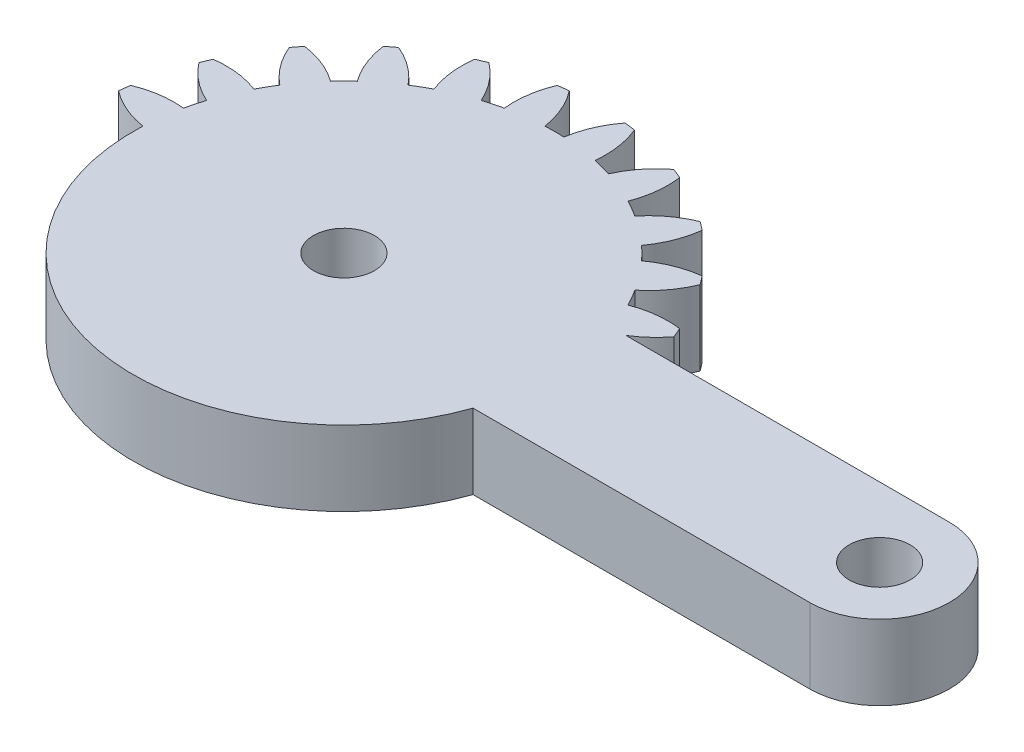
SolidWorks part; units mm, degrees
ref_plane "Front Plane" through (0, 0, 0) normal (0, 0, 1) x (1, 0, 0)
ref_plane "Top Plane" through (0, 0, 0) normal (0, 1, 0) x (1, 0, 0)
ref_plane "Right Plane" through (0, 0, 0) normal (1, 0, 0) x (0, 0, -1)
sketch "Sketch1" plane through (0, 0, 0) normal (0, 1, 0) x (1, 0, 0)
  line L0 (20.6437, 4) -> (2.0816, 4)
  line L1 (2.0816, -4) -> (20.6437, -4)
  arc A0 (2.0816, 4) -> (3.5217, 5.3071) centre (-0.7683, 8.5867) ccw
  arc A1 (3.5217, 5.3071) -> (3.2829, 5.8838) centre (-10.1063, 0) ccw
  arc A2 (3.2829, 5.8838) -> (0.6271, 5.5703) centre (2.5684, 0.5313) ccw
  arc A3 (0.6271, 5.5703) -> (0.0844, 6.5103) centre (-10.1063, 0) ccw
  arc A4 (0.0844, 6.5103) -> (1.6838, 8.6535) centre (-3.3089, 10.711) ccw
  arc A5 (1.6838, 8.6535) -> (1.3038, 9.1487) centre (-10.1063, 0) ccw
  arc A6 (1.3038, 9.1487) -> (-1.1803, 8.1585) centre (1.999, 3.7936) ccw
  arc A7 (-1.1803, 8.1585) -> (-1.9479, 8.926) centre (-10.1063, 0) ccw
  arc A8 (-1.9479, 8.926) -> (-0.9576, 11.4102) centre (-6.3127, 12.1053) ccw
  arc A9 (-0.9576, 11.4102) -> (-1.4528, 11.7901) centre (-10.1063, 0) ccw
  arc A10 (-1.4528, 11.7901) -> (-3.596, 10.1907) centre (0.6046, 6.7975) ccw
  arc A11 (-3.596, 10.1907) -> (-4.5361, 10.7334) centre (-10.1063, 0) ccw
  arc A12 (-4.5361, 10.7334) -> (-4.2225, 13.3892) centre (-9.5751, 12.6747) ccw
  arc A13 (-4.2225, 13.3892) -> (-4.7992, 13.6281) centre (-10.1063, 0) ccw
  arc A14 (-4.7992, 13.6281) -> (-6.4554, 11.5285) centre (-1.5196, 9.3381) ccw
  arc A15 (-6.4554, 11.5285) -> (-7.5039, 11.8094) centre (-10.1063, 0) ccw
  arc A16 (-7.5039, 11.8094) -> (-7.8884, 14.4558) centre (-12.8736, 12.3803) ccw
  arc A17 (-7.8884, 14.4558) -> (-8.5072, 14.5373) centre (-10.1063, 0) ccw
  arc A18 (-8.5072, 14.5373) -> (-9.5636, 12.0806) centre (-4.2291, 11.2423) ccw
  arc A19 (-9.5636, 12.0806) -> (-10.6491, 12.0806) centre (-10.1063, 0) ccw
  arc A20 (-10.6491, 12.0806) -> (-11.7054, 14.5373) centre (-15.9836, 11.2423) ccw
  arc A21 (-11.7054, 14.5373) -> (-12.3243, 14.4558) centre (-10.1063, 0) ccw
  arc A22 (-12.3243, 14.4558) -> (-12.7088, 11.8094) centre (-7.3391, 12.3803) ccw
  arc A23 (-12.7088, 11.8094) -> (-13.7573, 11.5285) centre (-10.1063, 0) ccw
  arc A24 (-13.7573, 11.5285) -> (-15.4135, 13.6281) centre (-18.6931, 9.3381) ccw
  arc A25 (-15.4135, 13.6281) -> (-15.9901, 13.3892) centre (-10.1063, 0) ccw
  arc A26 (-15.9901, 13.3892) -> (-15.6766, 10.7334) centre (-10.6376, 12.6747) ccw
  arc A27 (-15.6766, 10.7334) -> (-16.6166, 10.1907) centre (-10.1063, 0) ccw
  arc A28 (-16.6166, 10.1907) -> (-18.7599, 11.7901) centre (-20.8173, 6.7975) ccw
  arc A29 (-18.7599, 11.7901) -> (-19.255, 11.4102) centre (-10.1063, 0) ccw
  arc A30 (-19.255, 11.4102) -> (-18.2648, 8.926) centre (-13.9, 12.1053) ccw
  arc A31 (-18.2648, 8.926) -> (-19.0324, 8.1585) centre (-10.1063, 0) ccw
  arc A32 (-19.0324, 8.1585) -> (-21.5165, 9.1487) centre (-22.2117, 3.7936) ccw
  arc A33 (-21.5165, 9.1487) -> (-21.8965, 8.6535) centre (-10.1063, 0) ccw
  arc A34 (-21.8965, 8.6535) -> (-20.2971, 6.5103) centre (-16.9038, 10.711) ccw
  arc A35 (-20.2971, 6.5103) -> (-20.8398, 5.5703) centre (-10.1063, 0) ccw
  arc A36 (-20.8398, 5.5703) -> (-23.4956, 5.8838) centre (-22.7811, 0.5313) ccw
  arc A37 (-23.4956, 5.8838) -> (-23.7344, 5.3071) centre (-10.1063, 0) ccw
  arc A38 (-23.7344, 5.3071) -> (-21.6348, 3.6509) centre (-19.4444, 8.5867) ccw
  arc A39 (-21.6348, 3.6509) -> (-21.9157, 2.6025) centre (-10.1063, 0) ccw
  arc A40 (-21.9157, 2.6025) -> (-24.5622, 2.2179) centre (-22.4867, -2.7673) ccw
  arc A41 (-24.5622, 2.2179) -> (-24.6437, 1.5991) centre (-10.1063, 0) ccw
  arc A42 (-24.6437, 1.5991) -> (-22.1869, 0.5427) centre (-21.3486, 5.8773) ccw
  arc A43 (-22.1869, 0.5427) -> (-22.1869, -0.5427) centre (-10.1063, 0) ccw
  arc A44 (-22.1869, -0.5427) -> (-24.6437, -1.5991) centre (-21.3486, -5.8773) ccw
  arc A45 (-24.6437, -1.5991) -> (-24.5622, -2.2179) centre (-10.1063, 0) ccw
  arc A46 (-24.5622, -2.2179) -> (-21.9157, -2.6025) centre (-22.4867, 2.7673) ccw
  arc A47 (-21.9157, -2.6025) -> (-21.6348, -3.6509) centre (-10.1063, 0) ccw
  arc A48 (-21.6348, -3.6509) -> (-23.7344, -5.3071) centre (-19.4444, -8.5867) ccw
  arc A49 (-23.7344, -5.3071) -> (-23.4956, -5.8838) centre (-10.1063, 0) ccw
  arc A50 (-23.4956, -5.8838) -> (-20.8398, -5.5703) centre (-22.7811, -0.5313) ccw
  arc A51 (-20.8398, -5.5703) -> (-20.2971, -6.5103) centre (-10.1063, 0) ccw
  arc A52 (-20.2971, -6.5103) -> (-21.8965, -8.6535) centre (-16.9038, -10.711) ccw
  arc A53 (-21.8965, -8.6535) -> (-21.5165, -9.1487) centre (-10.1063, 0) ccw
  arc A54 (-21.5165, -9.1487) -> (-19.0324, -8.1585) centre (-22.2117, -3.7936) ccw
  arc A55 (-19.0324, -8.1585) -> (-18.2648, -8.926) centre (-10.1063, 0) ccw
  arc A56 (-18.2648, -8.926) -> (-19.255, -11.4102) centre (-13.9, -12.1053) ccw
  arc A57 (-19.255, -11.4102) -> (-18.7599, -11.7901) centre (-10.1063, 0) ccw
  arc A58 (-18.7599, -11.7901) -> (-16.6166, -10.1907) centre (-20.8173, -6.7975) ccw
  arc A59 (-16.6166, -10.1907) -> (-15.6766, -10.7334) centre (-10.1063, 0) ccw
  arc A60 (-15.6766, -10.7334) -> (-15.9901, -13.3892) centre (-10.6376, -12.6747) ccw
  arc A61 (-15.9901, -13.3892) -> (-15.4135, -13.6281) centre (-10.1063, 0) ccw
  arc A62 (-15.4135, -13.6281) -> (-13.7573, -11.5285) centre (-18.6931, -9.3381) ccw
  arc A63 (-13.7573, -11.5285) -> (-12.7088, -11.8094) centre (-10.1063, 0) ccw
  arc A64 (-12.7088, -11.8094) -> (-12.3243, -14.4558) centre (-7.3391, -12.3803) ccw
  arc A65 (-12.3243, -14.4558) -> (-11.7054, -14.5373) centre (-10.1063, 0) ccw
  arc A66 (-11.7054, -14.5373) -> (-10.6491, -12.0806) centre (-15.9836, -11.2423) ccw
  arc A67 (-10.6491, -12.0806) -> (-9.5636, -12.0806) centre (-10.1063, 0) ccw
  arc A68 (-9.5636, -12.0806) -> (-8.5072, -14.5373) centre (-4.2291, -11.2423) ccw
  arc A69 (-8.5072, -14.5373) -> (-7.8884, -14.4558) centre (-10.1063, 0) ccw
  arc A70 (-7.8884, -14.4558) -> (-7.5039, -11.8094) centre (-12.8736, -12.3803) ccw
  arc A71 (-7.5039, -11.8094) -> (-6.4554, -11.5285) centre (-10.1063, 0) ccw
  arc A72 (-6.4554, -11.5285) -> (-4.7992, -13.6281) centre (-1.5196, -9.3381) ccw
  arc A73 (-4.7992, -13.6281) -> (-4.2225, -13.3892) centre (-10.1063, 0) ccw
  arc A74 (-4.2225, -13.3892) -> (-4.5361, -10.7334) centre (-9.5751, -12.6747) ccw
  arc A75 (-4.5361, -10.7334) -> (-3.596, -10.1907) centre (-10.1063, 0) ccw
  arc A76 (-3.596, -10.1907) -> (-1.4528, -11.7901) centre (0.6046, -6.7975) ccw
  arc A77 (-1.4528, -11.7901) -> (-0.9576, -11.4102) centre (-10.1063, 0) ccw
  arc A78 (-0.9576, -11.4102) -> (-1.9479, -8.926) centre (-6.3127, -12.1053) ccw
  arc A79 (-1.9479, -8.926) -> (-1.1803, -8.1585) centre (-10.1063, 0) ccw
  arc A80 (-1.1803, -8.1585) -> (1.3038, -9.1487) centre (1.999, -3.7936) ccw
  arc A81 (1.3038, -9.1487) -> (1.6838, -8.6535) centre (-10.1063, 0) ccw
  arc A82 (1.6838, -8.6535) -> (0.0844, -6.5103) centre (-3.3089, -10.711) ccw
  arc A83 (0.0844, -6.5103) -> (0.6271, -5.5703) centre (-10.1063, 0) ccw
  arc A84 (0.6271, -5.5703) -> (3.2829, -5.8838) centre (2.5684, -0.5313) ccw
  arc A85 (3.2829, -5.8838) -> (3.5217, -5.3071) centre (-10.1063, 0) ccw
  arc A86 (3.5217, -5.3071) -> (2.0816, -4) centre (-0.7683, -8.5867) ccw
  arc A87 (20.6437, -4) -> (20.6437, 4) centre (20.6437, 0) ccw
  circle A88 centre (-10.1063, 0) radius 1.75
  circle A89 centre (20.6437, 0) radius 1.75
  dimension "D1" = 3.5
  dimension "D2" = 3.5
extrude "Boss-Extrude1" add sketch "Sketch1" along normal blind 4.3
sketch "Sketch2" plane through (0, 4.3, 0) normal (0, 1, 0) x (1, 0, 0)
  line L0 (2.0816, -4) -> (1.3057, -4)
  line L2 (20.6437, 4) -> (2.0816, 4)
  line L3 (2.0816, -4) -> (20.6437, -4)
  line L4 (20.6437, 4) -> (2.0816, 4)
  line L5 (2.0816, -4) -> (20.6437, -4)
  circle A0 centre (-10.1063, 0) radius 12.0927
  arc A88 (20.6437, -4) -> (20.6437, 4) centre (20.6437, 0) ccw
  arc A89 (2.0816, 4) -> (3.5217, 5.3071) centre (-0.7683, 8.5867) ccw
  arc A90 (3.5217, 5.3071) -> (3.2829, 5.8838) centre (-10.1063, 0) ccw
  arc A91 (3.2829, 5.8838) -> (0.6271, 5.5703) centre (2.5684, 0.5313) ccw
  arc A92 (0.6271, 5.5703) -> (0.0844, 6.5103) centre (-10.1063, 0) ccw
  arc A93 (0.0844, 6.5103) -> (1.6838, 8.6535) centre (-3.3089, 10.711) ccw
  arc A94 (1.6838, 8.6535) -> (1.3038, 9.1487) centre (-10.1063, 0) ccw
  arc A95 (1.3038, 9.1487) -> (-1.1803, 8.1585) centre (1.999, 3.7936) ccw
  arc A96 (-1.1803, 8.1585) -> (-1.9479, 8.926) centre (-10.1063, 0) ccw
  arc A97 (-1.9479, 8.926) -> (-0.9576, 11.4102) centre (-6.3127, 12.1053) ccw
  arc A98 (-0.9576, 11.4102) -> (-1.4528, 11.7901) centre (-10.1063, 0) ccw
  arc A99 (-1.4528, 11.7901) -> (-3.596, 10.1907) centre (0.6046, 6.7975) ccw
  arc A100 (-3.596, 10.1907) -> (-4.5361, 10.7334) centre (-10.1063, 0) ccw
  arc A101 (-4.5361, 10.7334) -> (-4.2225, 13.3892) centre (-9.5751, 12.6747) ccw
  arc A102 (-4.2225, 13.3892) -> (-4.7992, 13.6281) centre (-10.1063, 0) ccw
  arc A103 (-4.7992, 13.6281) -> (-6.4554, 11.5285) centre (-1.5196, 9.3381) ccw
  arc A104 (-6.4554, 11.5285) -> (-7.5039, 11.8094) centre (-10.1063, 0) ccw
  arc A105 (-7.5039, 11.8094) -> (-7.8884, 14.4558) centre (-12.8736, 12.3803) ccw
  arc A106 (-7.8884, 14.4558) -> (-8.5072, 14.5373) centre (-10.1063, 0) ccw
  arc A107 (-8.5072, 14.5373) -> (-9.5636, 12.0806) centre (-4.2291, 11.2423) ccw
  arc A108 (-9.5636, 12.0806) -> (-10.6491, 12.0806) centre (-10.1063, 0) ccw
  arc A109 (-10.6491, 12.0806) -> (-11.7054, 14.5373) centre (-15.9836, 11.2423) ccw
  arc A110 (-11.7054, 14.5373) -> (-12.3243, 14.4558) centre (-10.1063, 0) ccw
  arc A111 (-12.3243, 14.4558) -> (-12.7088, 11.8094) centre (-7.3391, 12.3803) ccw
  arc A112 (-12.7088, 11.8094) -> (-13.7573, 11.5285) centre (-10.1063, 0) ccw
  arc A113 (-13.7573, 11.5285) -> (-15.4135, 13.6281) centre (-18.6931, 9.3381) ccw
  arc A114 (-15.4135, 13.6281) -> (-15.9901, 13.3892) centre (-10.1063, 0) ccw
  arc A115 (-15.9901, 13.3892) -> (-15.6766, 10.7334) centre (-10.6376, 12.6747) ccw
  arc A116 (-15.6766, 10.7334) -> (-16.6166, 10.1907) centre (-10.1063, 0) ccw
  arc A117 (-16.6166, 10.1907) -> (-18.7599, 11.7901) centre (-20.8173, 6.7975) ccw
  arc A118 (-18.7599, 11.7901) -> (-19.255, 11.4102) centre (-10.1063, 0) ccw
  arc A119 (-19.255, 11.4102) -> (-18.2648, 8.926) centre (-13.9, 12.1053) ccw
  arc A120 (-18.2648, 8.926) -> (-19.0324, 8.1585) centre (-10.1063, 0) ccw
  arc A121 (-19.0324, 8.1585) -> (-21.5165, 9.1487) centre (-22.2117, 3.7936) ccw
  arc A122 (-21.5165, 9.1487) -> (-21.8965, 8.6535) centre (-10.1063, 0) ccw
  arc A123 (-21.8965, 8.6535) -> (-20.2971, 6.5103) centre (-16.9038, 10.711) ccw
  arc A124 (-20.2971, 6.5103) -> (-20.8398, 5.5703) centre (-10.1063, 0) ccw
  arc A125 (-20.8398, 5.5703) -> (-23.4956, 5.8838) centre (-22.7811, 0.5313) ccw
  arc A126 (-23.4956, 5.8838) -> (-23.7344, 5.3071) centre (-10.1063, 0) ccw
  arc A127 (-23.7344, 5.3071) -> (-21.6348, 3.6509) centre (-19.4444, 8.5867) ccw
  arc A128 (-21.6348, 3.6509) -> (-21.9157, 2.6025) centre (-10.1063, 0) ccw
  arc A129 (-21.9157, 2.6025) -> (-24.5622, 2.2179) centre (-22.4867, -2.7673) ccw
  arc A130 (-24.5622, 2.2179) -> (-24.6437, 1.5991) centre (-10.1063, 0) ccw
  arc A131 (-24.6437, 1.5991) -> (-22.1869, 0.5427) centre (-21.3486, 5.8773) ccw
  arc A132 (-22.1869, 0.5427) -> (-22.1869, -0.5427) centre (-10.1063, 0) ccw
  arc A133 (-22.1869, -0.5427) -> (-24.6437, -1.5991) centre (-21.3486, -5.8773) ccw
  arc A134 (-24.6437, -1.5991) -> (-24.5622, -2.2179) centre (-10.1063, 0) ccw
  arc A135 (-24.5622, -2.2179) -> (-21.9157, -2.6025) centre (-22.4867, 2.7673) ccw
  arc A136 (-21.9157, -2.6025) -> (-21.6348, -3.6509) centre (-10.1063, 0) ccw
  arc A137 (-21.6348, -3.6509) -> (-23.7344, -5.3071) centre (-19.4444, -8.5867) ccw
  arc A138 (-23.7344, -5.3071) -> (-23.4956, -5.8838) centre (-10.1063, 0) ccw
  arc A139 (-23.4956, -5.8838) -> (-20.8398, -5.5703) centre (-22.7811, -0.5313) ccw
  arc A140 (-20.8398, -5.5703) -> (-20.2971, -6.5103) centre (-10.1063, 0) ccw
  arc A141 (-20.2971, -6.5103) -> (-21.8965, -8.6535) centre (-16.9038, -10.711) ccw
  arc A142 (-21.8965, -8.6535) -> (-21.5165, -9.1487) centre (-10.1063, 0) ccw
  arc A143 (-21.5165, -9.1487) -> (-19.0324, -8.1585) centre (-22.2117, -3.7936) ccw
  arc A144 (-19.0324, -8.1585) -> (-18.2648, -8.926) centre (-10.1063, 0) ccw
  arc A145 (-18.2648, -8.926) -> (-19.255, -11.4102) centre (-13.9, -12.1053) ccw
  arc A146 (-19.255, -11.4102) -> (-18.7599, -11.7901) centre (-10.1063, 0) ccw
  arc A147 (-18.7599, -11.7901) -> (-16.6166, -10.1907) centre (-20.8173, -6.7975) ccw
  arc A148 (-16.6166, -10.1907) -> (-15.6766, -10.7334) centre (-10.1063, 0) ccw
  arc A149 (-15.6766, -10.7334) -> (-15.9901, -13.3892) centre (-10.6376, -12.6747) ccw
  arc A150 (-15.9901, -13.3892) -> (-15.4135, -13.6281) centre (-10.1063, 0) ccw
  arc A151 (-15.4135, -13.6281) -> (-13.7573, -11.5285) centre (-18.6931, -9.3381) ccw
  arc A152 (-13.7573, -11.5285) -> (-12.7088, -11.8094) centre (-10.1063, 0) ccw
  arc A153 (-12.7088, -11.8094) -> (-12.3243, -14.4558) centre (-7.3391, -12.3803) ccw
  arc A154 (-12.3243, -14.4558) -> (-11.7054, -14.5373) centre (-10.1063, 0) ccw
  arc A155 (-11.7054, -14.5373) -> (-10.6491, -12.0806) centre (-15.9836, -11.2423) ccw
  arc A156 (-10.6491, -12.0806) -> (-9.5636, -12.0806) centre (-10.1063, 0) ccw
  arc A157 (-9.5636, -12.0806) -> (-8.5072, -14.5373) centre (-4.2291, -11.2423) ccw
  arc A158 (-8.5072, -14.5373) -> (-7.8884, -14.4558) centre (-10.1063, 0) ccw
  arc A159 (-7.8884, -14.4558) -> (-7.5039, -11.8094) centre (-12.8736, -12.3803) ccw
  arc A160 (-7.5039, -11.8094) -> (-6.4554, -11.5285) centre (-10.1063, 0) ccw
  arc A161 (-6.4554, -11.5285) -> (-4.7992, -13.6281) centre (-1.5196, -9.3381) ccw
  arc A162 (-4.7992, -13.6281) -> (-4.2225, -13.3892) centre (-10.1063, 0) ccw
  arc A163 (-4.2225, -13.3892) -> (-4.5361, -10.7334) centre (-9.5751, -12.6747) ccw
  arc A164 (-4.5361, -10.7334) -> (-3.596, -10.1907) centre (-10.1063, 0) ccw
  arc A165 (-3.596, -10.1907) -> (-1.4528, -11.7901) centre (0.6046, -6.7975) ccw
  arc A166 (-1.4528, -11.7901) -> (-0.9576, -11.4102) centre (-10.1063, 0) ccw
  arc A167 (-0.9576, -11.4102) -> (-1.9479, -8.926) centre (-6.3127, -12.1053) ccw
  arc A168 (-1.9479, -8.926) -> (-1.1803, -8.1585) centre (-10.1063, 0) ccw
  arc A169 (-1.1803, -8.1585) -> (1.3038, -9.1487) centre (1.999, -3.7936) ccw
  arc A170 (1.3038, -9.1487) -> (1.6838, -8.6535) centre (-10.1063, 0) ccw
  arc A171 (1.6838, -8.6535) -> (0.0844, -6.5103) centre (-3.3089, -10.711) ccw
  arc A172 (0.0844, -6.5103) -> (0.6271, -5.5703) centre (-10.1063, 0) ccw
  arc A173 (0.6271, -5.5703) -> (3.2829, -5.8838) centre (2.5684, -0.5313) ccw
  arc A174 (3.2829, -5.8838) -> (3.5217, -5.3071) centre (-10.1063, 0) ccw
  arc A175 (3.5217, -5.3071) -> (2.0816, -4) centre (-0.7683, -8.5867) ccw
  arc A176 (20.6437, -4) -> (20.6437, 4) centre (20.6437, 0) ccw
  arc A177 (2.0816, 4) -> (3.5217, 5.3071) centre (-0.7683, 8.5867) ccw
  arc A178 (3.5217, 5.3071) -> (3.2829, 5.8838) centre (-10.1063, 0) ccw
  arc A179 (3.2829, 5.8838) -> (0.6271, 5.5703) centre (2.5684, 0.5313) ccw
  arc A180 (0.6271, 5.5703) -> (0.0844, 6.5103) centre (-10.1063, 0) ccw
  arc A181 (0.0844, 6.5103) -> (1.6838, 8.6535) centre (-3.3089, 10.711) ccw
  arc A182 (1.6838, 8.6535) -> (1.3038, 9.1487) centre (-10.1063, 0) ccw
  arc A183 (1.3038, 9.1487) -> (-1.1803, 8.1585) centre (1.999, 3.7936) ccw
  arc A184 (-1.1803, 8.1585) -> (-1.9479, 8.926) centre (-10.1063, 0) ccw
  arc A185 (-1.9479, 8.926) -> (-0.9576, 11.4102) centre (-6.3127, 12.1053) ccw
  arc A186 (-0.9576, 11.4102) -> (-1.4528, 11.7901) centre (-10.1063, 0) ccw
  arc A187 (-1.4528, 11.7901) -> (-3.596, 10.1907) centre (0.6046, 6.7975) ccw
  arc A188 (-3.596, 10.1907) -> (-4.5361, 10.7334) centre (-10.1063, 0) ccw
  arc A189 (-4.5361, 10.7334) -> (-4.2225, 13.3892) centre (-9.5751, 12.6747) ccw
  arc A190 (-4.2225, 13.3892) -> (-4.7992, 13.6281) centre (-10.1063, 0) ccw
  arc A191 (-4.7992, 13.6281) -> (-6.4554, 11.5285) centre (-1.5196, 9.3381) ccw
  arc A192 (-6.4554, 11.5285) -> (-7.5039, 11.8094) centre (-10.1063, 0) ccw
  arc A193 (-7.5039, 11.8094) -> (-7.8884, 14.4558) centre (-12.8736, 12.3803) ccw
  arc A194 (-7.8884, 14.4558) -> (-8.5072, 14.5373) centre (-10.1063, 0) ccw
  arc A195 (-8.5072, 14.5373) -> (-9.5636, 12.0806) centre (-4.2291, 11.2423) ccw
  arc A196 (-9.5636, 12.0806) -> (-10.6491, 12.0806) centre (-10.1063, 0) ccw
  arc A197 (-10.6491, 12.0806) -> (-11.7054, 14.5373) centre (-15.9836, 11.2423) ccw
  arc A198 (-11.7054, 14.5373) -> (-12.3243, 14.4558) centre (-10.1063, 0) ccw
  arc A199 (-12.3243, 14.4558) -> (-12.7088, 11.8094) centre (-7.3391, 12.3803) ccw
  arc A200 (-12.7088, 11.8094) -> (-13.7573, 11.5285) centre (-10.1063, 0) ccw
  arc A201 (-13.7573, 11.5285) -> (-15.4135, 13.6281) centre (-18.6931, 9.3381) ccw
  arc A202 (-15.4135, 13.6281) -> (-15.9901, 13.3892) centre (-10.1063, 0) ccw
  arc A203 (-15.9901, 13.3892) -> (-15.6766, 10.7334) centre (-10.6376, 12.6747) ccw
  arc A204 (-15.6766, 10.7334) -> (-16.6166, 10.1907) centre (-10.1063, 0) ccw
  arc A205 (-16.6166, 10.1907) -> (-18.7599, 11.7901) centre (-20.8173, 6.7975) ccw
  arc A206 (-18.7599, 11.7901) -> (-19.255, 11.4102) centre (-10.1063, 0) ccw
  arc A207 (-19.255, 11.4102) -> (-18.2648, 8.926) centre (-13.9, 12.1053) ccw
  arc A208 (-18.2648, 8.926) -> (-19.0324, 8.1585) centre (-10.1063, 0) ccw
  arc A209 (-19.0324, 8.1585) -> (-21.5165, 9.1487) centre (-22.2117, 3.7936) ccw
  arc A210 (-21.5165, 9.1487) -> (-21.8965, 8.6535) centre (-10.1063, 0) ccw
  arc A211 (-21.8965, 8.6535) -> (-20.2971, 6.5103) centre (-16.9038, 10.711) ccw
  arc A212 (-20.2971, 6.5103) -> (-20.8398, 5.5703) centre (-10.1063, 0) ccw
  arc A213 (-20.8398, 5.5703) -> (-23.4956, 5.8838) centre (-22.7811, 0.5313) ccw
  arc A214 (-23.4956, 5.8838) -> (-23.7344, 5.3071) centre (-10.1063, 0) ccw
  arc A215 (-23.7344, 5.3071) -> (-21.6348, 3.6509) centre (-19.4444, 8.5867) ccw
  arc A216 (-21.6348, 3.6509) -> (-21.9157, 2.6025) centre (-10.1063, 0) ccw
  arc A217 (-21.9157, 2.6025) -> (-24.5622, 2.2179) centre (-22.4867, -2.7673) ccw
  arc A218 (-24.5622, 2.2179) -> (-24.6437, 1.5991) centre (-10.1063, 0) ccw
  arc A219 (-24.6437, 1.5991) -> (-22.1869, 0.5427) centre (-21.3486, 5.8773) ccw
  arc A220 (-22.1869, 0.5427) -> (-22.1869, -0.5427) centre (-10.1063, 0) ccw
  arc A221 (-22.1869, -0.5427) -> (-24.6437, -1.5991) centre (-21.3486, -5.8773) ccw
  arc A222 (-24.6437, -1.5991) -> (-24.5622, -2.2179) centre (-10.1063, 0) ccw
  arc A223 (-24.5622, -2.2179) -> (-21.9157, -2.6025) centre (-22.4867, 2.7673) ccw
  arc A224 (-21.9157, -2.6025) -> (-21.6348, -3.6509) centre (-10.1063, 0) ccw
  arc A225 (-21.6348, -3.6509) -> (-23.7344, -5.3071) centre (-19.4444, -8.5867) ccw
  arc A226 (-23.7344, -5.3071) -> (-23.4956, -5.8838) centre (-10.1063, 0) ccw
  arc A227 (-23.4956, -5.8838) -> (-20.8398, -5.5703) centre (-22.7811, -0.5313) ccw
  arc A228 (-20.8398, -5.5703) -> (-20.2971, -6.5103) centre (-10.1063, 0) ccw
  arc A229 (-20.2971, -6.5103) -> (-21.8965, -8.6535) centre (-16.9038, -10.711) ccw
  arc A230 (-21.8965, -8.6535) -> (-21.5165, -9.1487) centre (-10.1063, 0) ccw
  arc A231 (-21.5165, -9.1487) -> (-19.0324, -8.1585) centre (-22.2117, -3.7936) ccw
  arc A232 (-19.0324, -8.1585) -> (-18.2648, -8.926) centre (-10.1063, 0) ccw
  arc A233 (-18.2648, -8.926) -> (-19.255, -11.4102) centre (-13.9, -12.1053) ccw
  arc A234 (-19.255, -11.4102) -> (-18.7599, -11.7901) centre (-10.1063, 0) ccw
  arc A235 (-18.7599, -11.7901) -> (-16.6166, -10.1907) centre (-20.8173, -6.7975) ccw
  arc A236 (-16.6166, -10.1907) -> (-15.6766, -10.7334) centre (-10.1063, 0) ccw
  arc A237 (-15.6766, -10.7334) -> (-15.9901, -13.3892) centre (-10.6376, -12.6747) ccw
  arc A238 (-15.9901, -13.3892) -> (-15.4135, -13.6281) centre (-10.1063, 0) ccw
  arc A239 (-15.4135, -13.6281) -> (-13.7573, -11.5285) centre (-18.6931, -9.3381) ccw
  arc A240 (-13.7573, -11.5285) -> (-12.7088, -11.8094) centre (-10.1063, 0) ccw
  arc A241 (-12.7088, -11.8094) -> (-12.3243, -14.4558) centre (-7.3391, -12.3803) ccw
  arc A242 (-12.3243, -14.4558) -> (-11.7054, -14.5373) centre (-10.1063, 0) ccw
  arc A243 (-11.7054, -14.5373) -> (-10.6491, -12.0806) centre (-15.9836, -11.2423) ccw
  arc A244 (-10.6491, -12.0806) -> (-9.5636, -12.0806) centre (-10.1063, 0) ccw
  arc A245 (-9.5636, -12.0806) -> (-8.5072, -14.5373) centre (-4.2291, -11.2423) ccw
  arc A246 (-8.5072, -14.5373) -> (-7.8884, -14.4558) centre (-10.1063, 0) ccw
  arc A247 (-7.8884, -14.4558) -> (-7.5039, -11.8094) centre (-12.8736, -12.3803) ccw
  arc A248 (-7.5039, -11.8094) -> (-6.4554, -11.5285) centre (-10.1063, 0) ccw
  arc A249 (-6.4554, -11.5285) -> (-4.7992, -13.6281) centre (-1.5196, -9.3381) ccw
  arc A250 (-4.7992, -13.6281) -> (-4.2225, -13.3892) centre (-10.1063, 0) ccw
  arc A251 (-4.2225, -13.3892) -> (-4.5361, -10.7334) centre (-9.5751, -12.6747) ccw
  arc A252 (-4.5361, -10.7334) -> (-3.596, -10.1907) centre (-10.1063, 0) ccw
  arc A253 (-3.596, -10.1907) -> (-1.4528, -11.7901) centre (0.6046, -6.7975) ccw
  arc A254 (-1.4528, -11.7901) -> (-0.9576, -11.4102) centre (-10.1063, 0) ccw
  arc A255 (-0.9576, -11.4102) -> (-1.9479, -8.926) centre (-6.3127, -12.1053) ccw
  arc A256 (-1.9479, -8.926) -> (-1.1803, -8.1585) centre (-10.1063, 0) ccw
  arc A257 (-1.1803, -8.1585) -> (1.3038, -9.1487) centre (1.999, -3.7936) ccw
  arc A258 (1.3038, -9.1487) -> (1.6838, -8.6535) centre (-10.1063, 0) ccw
  arc A259 (1.6838, -8.6535) -> (0.0844, -6.5103) centre (-3.3089, -10.711) ccw
  arc A260 (0.0844, -6.5103) -> (0.6271, -5.5703) centre (-10.1063, 0) ccw
  arc A261 (0.6271, -5.5703) -> (3.2829, -5.8838) centre (2.5684, -0.5313) ccw
  arc A262 (3.2829, -5.8838) -> (3.5217, -5.3071) centre (-10.1063, 0) ccw
  arc A263 (3.5217, -5.3071) -> (2.0816, -4) centre (-0.7683, -8.5867) ccw
  dimension "D1" = 0
extrude "Cut-Extrude1" cut sketch "Sketch2" against normal blind 10 contours A222 A223 A0 A221 | A226 A227 A0 A225 | A230 A231 A0 A229 | A234 A235 A0 A233 | A238 A239 A0 A237 | A242 A243 A0 A241 | A246 A247 A0 A245 | A250 A251 A0 A249 | A254 A255 A0 A253 | A258 A259 A0 A257 | A262 A263 L0 A0 A261
